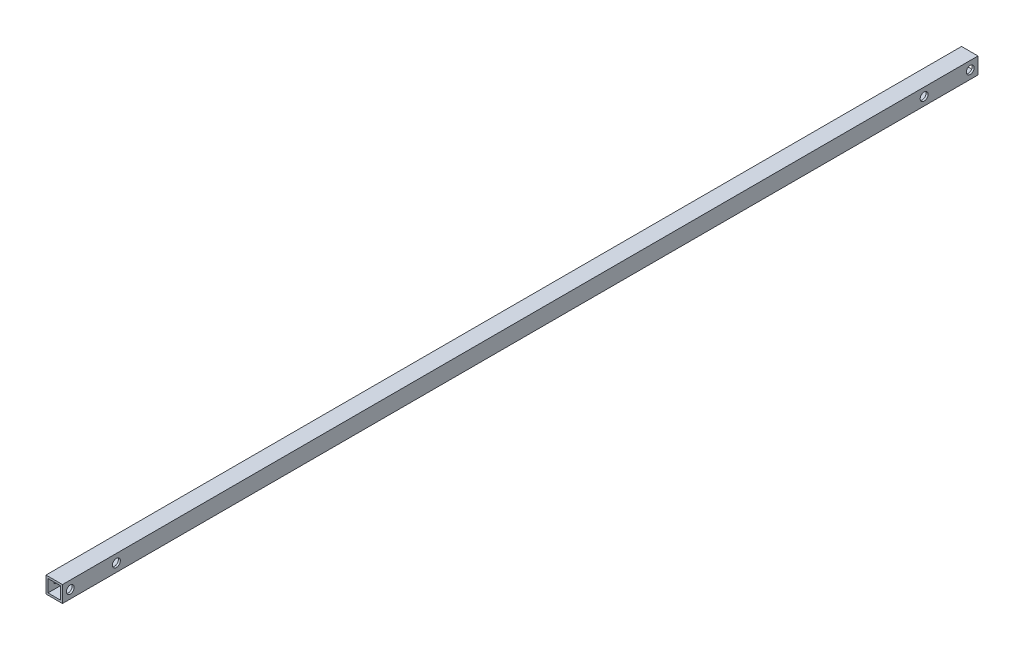
SolidWorks part; units mm, degrees
ref_plane "前视基准面" through (0, 0, 0) normal (0, 0, 1) x (1, 0, 0)
ref_plane "上视基准面" through (0, 0, 0) normal (0, 1, 0) x (1, 0, 0)
ref_plane "右视基准面" through (0, 0, 0) normal (1, 0, 0) x (0, 0, -1)
sketch "草图1" plane through (0, 0, 0) normal (0, 0, 1) x (1, 0, 0)
  line L1 (0, 0) -> (25, 0)
  line L2 (0, 0) -> (0, -25)
  line L3 (0, -25) -> (25, -25)
  line L4 (25, 0) -> (25, -25)
  line L5 (3, -3) -> (22, -3)
  line L6 (3, -3) -> (3, -22)
  line L7 (3, -22) -> (22, -22)
  line L8 (22, -3) -> (22, -22)
  dimension "D1" = 3
  dimension "D2" = 3
  dimension "D3" = 3
  dimension "D4" = 3
  dimension "D5" = 25
  dimension "D6" = 25
extrude "拉伸1" add sketch "草图1" along normal blind 1390
hole_wizard "Ø6.0 (6) 直径孔1" positions "草图5" profile "草图4" hole size "Ø6.0" standard "GB"
sketch "草图5" plane through (0, 0, 0) normal (-1, 0, 0) x (0, 0, 1)
  line L1 (0, -25) -> (0, 0) construction
  line L2 (1390, -25) -> (0, -25) construction
  point P0 (11.8, -12.5)
  point P1 (81.8, -12.5)
  dimension "D1" = 70
  dimension "D2" = 11.8
  dimension "D3" = 12.5
sketch "草图4" plane through (0, -12.5, 11.8) normal (0, 1, 0) x (0, 0, 1)
  line L0 (0, 0) -> (0, 31.8026)
  line L1 (0, 31.8026) -> (3, 30)
  line L2 (3, 30) -> (3, 0)
  line L5 (3, 0) -> (0, 0)
  line L10 (0, 31.8026) -> (-3, 30) construction
  line L11 (0, -6.35) -> (0, 107.95) construction
  dimension "孔直径" = 6
  dimension "孔深度" = 30
  dimension "导头角度" = 118
sketch "草图6" plane through (25, 0, 0) normal (1, 0, 0) x (0, 0, -1)
  circle A0 centre (-11.8, -12.5) radius 6
  circle A1 centre (-81.8, -12.5) radius 6
  dimension "D1" = 12
  dimension "D2" = 12
extrude "切除-拉伸1" cut sketch "草图6" against normal up to next
pattern_linear "阵列(线性)1" count 2 spacing 1296.34 along (0, 0, 1) of "Ø6.0 (6) 直径孔1", "切除-拉伸1"
